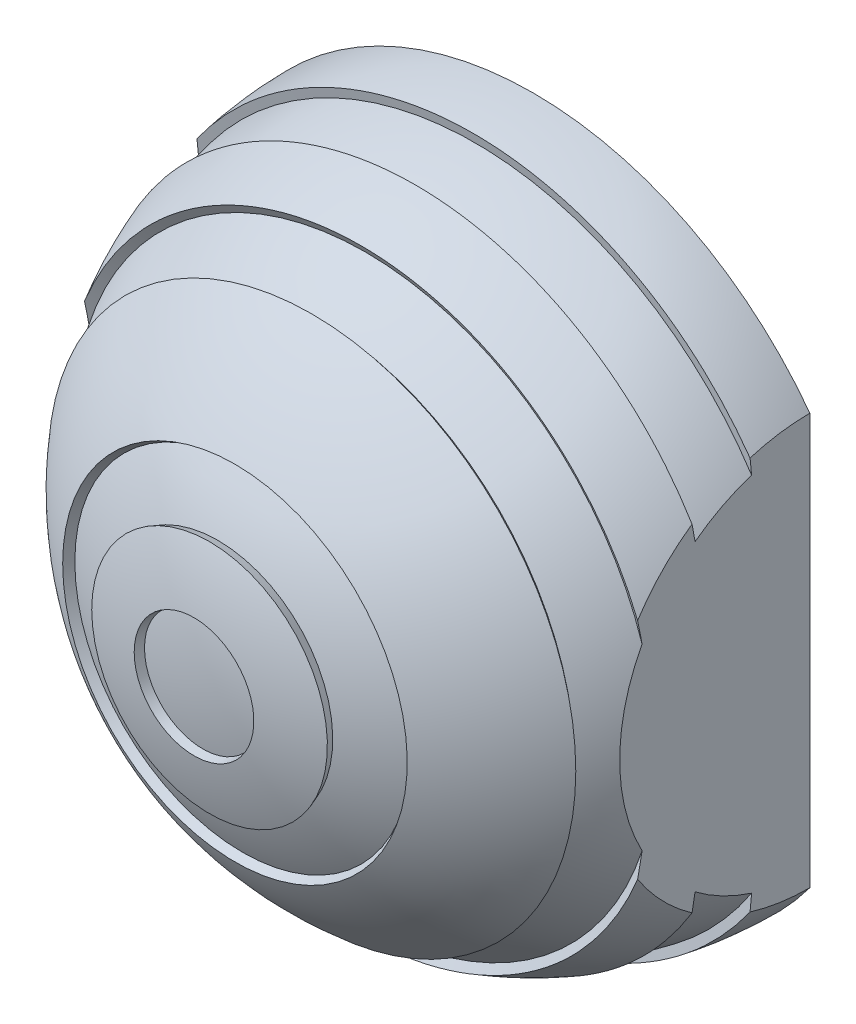
SolidWorks part; units mm, degrees
ref_plane "前视基准面" through (0, 0, 0) normal (0, 0, 1) x (1, 0, 0)
ref_plane "上视基准面" through (0, 0, 0) normal (0, 1, 0) x (1, 0, 0)
ref_plane "右视基准面" through (0, 0, 0) normal (1, 0, 0) x (0, 0, -1)
other "Configuration Table"
sketch "草图1" plane through (0, 0, 0) normal (0, 0, 1) x (1, 0, 0)
  line L0 (0, 25.15) -> (0, -25.15)
  arc A0 (0, -25.15) -> (0, 25.15) centre (0, 0) ccw
  dimension "D1" = 50.3
revolve "旋转1" add sketch "草图1" angle 180 about L0
sketch "草图2" plane through (0, 0, 0) normal (0, 0, -1) x (-1, 0, 0)
  line L0 (-20.1872, 15) -> (-20.1872, -15)
  line L1 (0, 25.15) -> (0, -25.15)
  line L2 (20.1872, 15) -> (20.1872, -15)
  circle A1 centre (0, 0) radius 25.15
  circle A2 centre (0, 0) radius 25.15
  circle M5 centre (0, 0) radius 25.15
  dimension "D2" = 30
  dimension "D3" = 30
  dimension "D1" = 0
extrude "切除-拉伸1" cut sketch "草图2" against normal through all contours L2 M5 | L0 M5
shell "抽壳1" thickness 5
sketch "草图3" plane through (0, 0, 0) normal (0, 0, -1) x (-1, 0, 0)
  line L2 (-15.1872, 13.2428) -> (-15.1872, -13.2428)
  line L3 (15.1872, -13.2428) -> (15.1872, 13.2428)
  line L4 (-15.1872, 13.2428) -> (-15.1872, -13.2428)
  line L5 (15.1872, -13.2428) -> (15.1872, 13.2428)
  circle A0 centre (0, 0) radius 1.5
  circle A1 centre (0, 0) radius 0.5
  arc A4 (15.1872, 13.2428) -> (-15.1872, 13.2428) centre (0, 0) ccw
  arc A5 (-15.1872, -13.2428) -> (15.1872, -13.2428) centre (0, 0) ccw
  arc A6 (15.1872, 13.2428) -> (-15.1872, 13.2428) centre (0, 0) ccw
  arc A7 (-15.1872, -13.2428) -> (15.1872, -13.2428) centre (0, 0) ccw
  arc M7 (-15.1872, 13.2428) -> (15.1872, 13.2428) centre (0, 0) cw
  line M8 (15.1872, 13.2428) -> (15.1872, -13.2428)
  arc M9 (15.1872, -13.2428) -> (-15.1872, -13.2428) centre (0, 0) cw
  line M10 (-15.1872, -13.2428) -> (-15.1872, 13.2428)
  dimension "D1" = 3
  dimension "D2" = 1
  dimension "D3" = 0
extrude "凸台-拉伸3" add sketch "草图3" against normal blind 5 contours A0 M7 M10 M9 M8 | A0 A1
sketch "草图5" plane through (0, 0, 0) normal (0, 0, -1) x (-1, 0, 0)
  line L2 (15.1872, -12.2626) -> (15.1872, 12.2626)
  line L3 (-15.1872, 12.2626) -> (-15.1872, -12.2626)
  line L4 (15.1872, -12.2626) -> (15.1872, 12.2626)
  line L5 (-15.1872, 12.2626) -> (-15.1872, -12.2626)
  circle A0 centre (0, 0) radius 1.5
  circle A1 centre (0, 0) radius 0.5 construction
  circle A2 centre (0, 0) radius 0.5
  arc A3 (15.1872, 12.2626) -> (-15.1872, 12.2626) centre (0, 0) ccw
  arc A4 (-15.1872, -12.2626) -> (15.1872, -12.2626) centre (0, 0) ccw
  arc A5 (15.1872, 12.2626) -> (-15.1872, 12.2626) centre (0, 0) ccw
  arc A6 (-15.1872, -12.2626) -> (15.1872, -12.2626) centre (0, 0) ccw
  circle M11 centre (0, 0) radius 0.5
  dimension "D2" = 3
  dimension "D1" = 0
extrude "凸台-拉伸4" add sketch "草图5" along normal blind 10 contours A0 M11
ref_plane "基准面1" through (0, 0, 0) normal (1, 0, 0) x (0, 0, -1)
sketch "草图6" plane through (0, 0, 0) normal (1, 0, 0) x (0, 0, -1)
  line L0 (0, 0) -> (-12.575, 21.7805)
  line L1 (0, 0) -> (-16.1661, 19.266)
  line L2 (0, 25.15) -> (0, -25.15)
  line L3 (0, -15) -> (0, 15)
  line L4 (0, -15) -> (0, 15)
  line L5 (0, 0) -> (-4.3673, 24.7679)
  line L6 (0, 0) -> (-25.15, 0)
  line L7 (0, 0) -> (-8.6018, 23.6333)
  line L8 (0, 0) -> (-19.266, 16.1661)
  line L9 (0, 0) -> (-21.7805, 12.575)
  line L10 (0, 0) -> (-23.6333, 8.6018)
  line L11 (0, 0) -> (-24.7679, 4.3673)
  line L12 (0, 0) -> (-24.7679, -4.3673)
  line L13 (0, 0) -> (-23.6333, -8.6018)
  line L14 (0, 0) -> (-21.7805, -12.575)
  line L15 (0, 0) -> (-19.266, -16.1661)
  line L16 (0, 0) -> (-16.1661, -19.266)
  line L17 (0, 0) -> (-12.575, -21.7805)
  line L18 (0, 0) -> (-8.6018, -23.6333)
  line L19 (0, 0) -> (-4.3673, -24.7679)
  arc A2 (0, 25.15) -> (0, -25.15) centre (0, 0) ccw
  arc A3 (0, 15) -> (0, -15) centre (0, 0) ccw
  arc A4 (0, 15) -> (0, -15) centre (0, 0) ccw construction
  arc A5 (0, 24.5) -> (0, -24.5) centre (0, 0) ccw
  dimension "D2" = 49
  dimension "D3" = 10
  dimension "D4" = 10
  dimension "D5" = 10
  dimension "D6" = 10
  dimension "D7" = 10
  dimension "D8" = 10
  dimension "D9" = 10
  dimension "D10" = 10
  dimension "D1" = 0
revolve "切除-旋转2" cut sketch "草图6" angle 360 about L6
sketch "草图7" plane through (0, 0, 0) normal (1, 0, 0) x (0, 0, -1)
  line L1 (-54.1745, 39.2347) -> (17.7334, 39.2347)
  line L2 (-54.1745, 39.2347) -> (-54.1745, -38.2973)
  line L3 (-54.1745, -38.2973) -> (17.7334, -38.2973)
  line L4 (17.7334, 39.2347) -> (17.7334, -38.2973)
